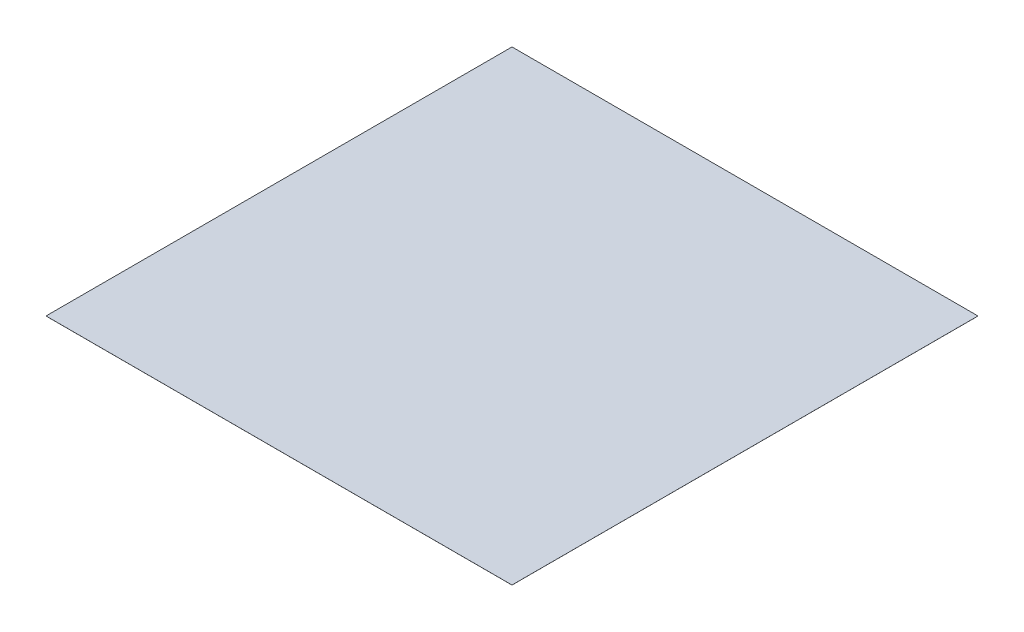
SolidWorks part; units mm, degrees
ref_plane "Front Plane" through (0, 0, 0) normal (0, 0, 1) x (1, 0, 0)
ref_plane "Top Plane" through (0, 0, 0) normal (0, 1, 0) x (1, 0, 0)
ref_plane "Right Plane" through (0, 0, 0) normal (1, 0, 0) x (0, 0, -1)
sketch "Sketch1" plane through (0, 0, 0) normal (0, 1, 0) x (1, 0, 0)
  line L1 (0, 0) -> (254, 0)
  line L2 (0, 0) -> (0, 254)
  line L3 (0, 254) -> (254, 254)
  line L4 (254, 0) -> (254, 254)
  dimension "D1" = 254
  dimension "D2" = 254
extrude "Boss-Extrude1" add sketch "Sketch1" along normal blind 0.0254
